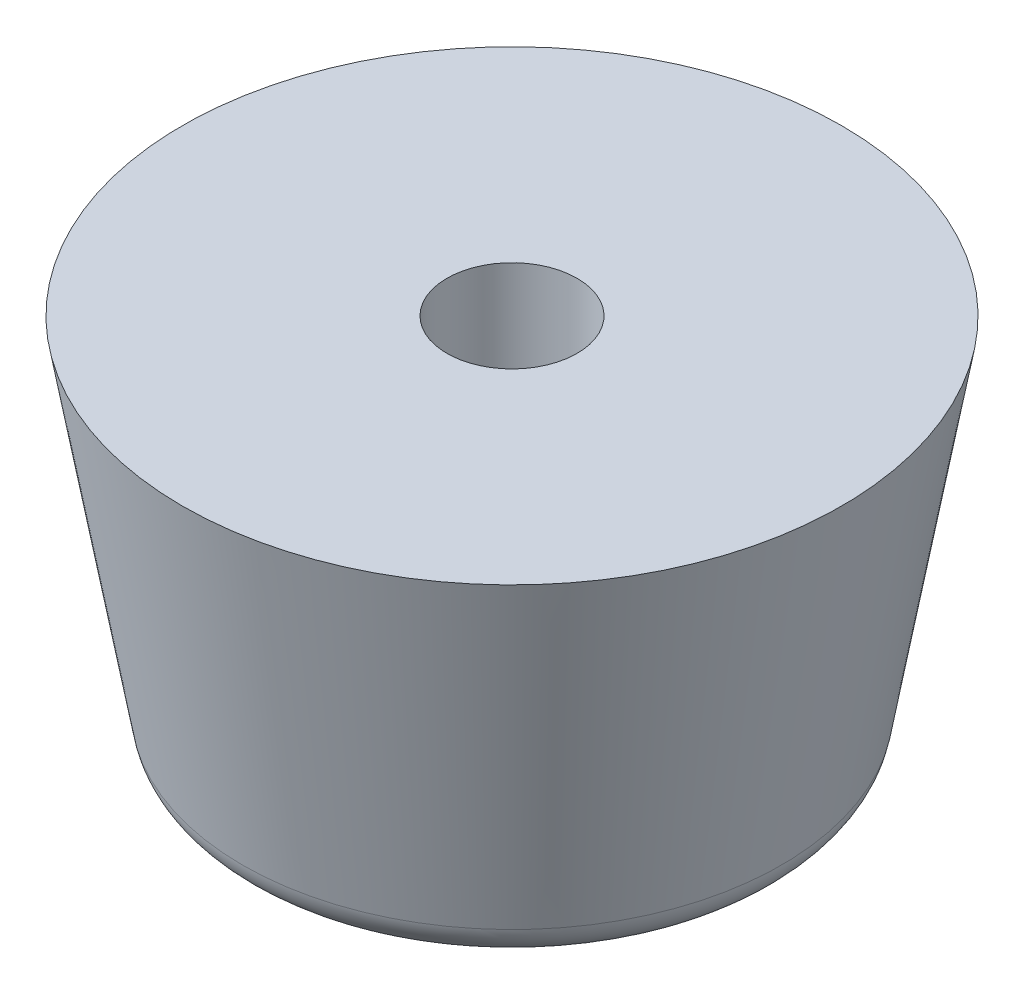
SolidWorks part; units mm, degrees
material "Rubber"
ref_plane "Plano frontal" through (0, 0, 0) normal (0, 0, 1) x (1, 0, 0)
ref_plane "Plano superior" through (0, 0, 0) normal (0, 1, 0) x (1, 0, 0)
ref_plane "Plano direito" through (0, 0, 0) normal (1, 0, 0) x (0, 0, -1)
sketch "Esboço1" plane through (0, 0, 0) normal (0, 1, 0) x (1, 0, 0)
  circle A0 centre (0, 0) radius 15.19
  dimension "D1" = 30.38
extrude "Ressalto-extrusão1" add sketch "Esboço1" against normal blind 17.37 draft 10
sketch "Esboço2" plane through (0, -17.37, 0) normal (0, -1, 0) x (1, 0, 0)
  circle A0 centre (0, 0) radius 5
  dimension "D1" = 10
extrude "Corte-extrusão1" cut sketch "Esboço2" against normal blind 7
sketch "Esboço3" plane through (0, -10.37, 0) normal (0, -1, 0) x (1, 0, 0)
  circle A0 centre (0, 0) radius 3
  dimension "D1" = 6
extrude "Corte-extrusão2" cut sketch "Esboço3" against normal through all
fillet "Filete1" radius 2 1 edges at (0, -17.37, 12.1272)
